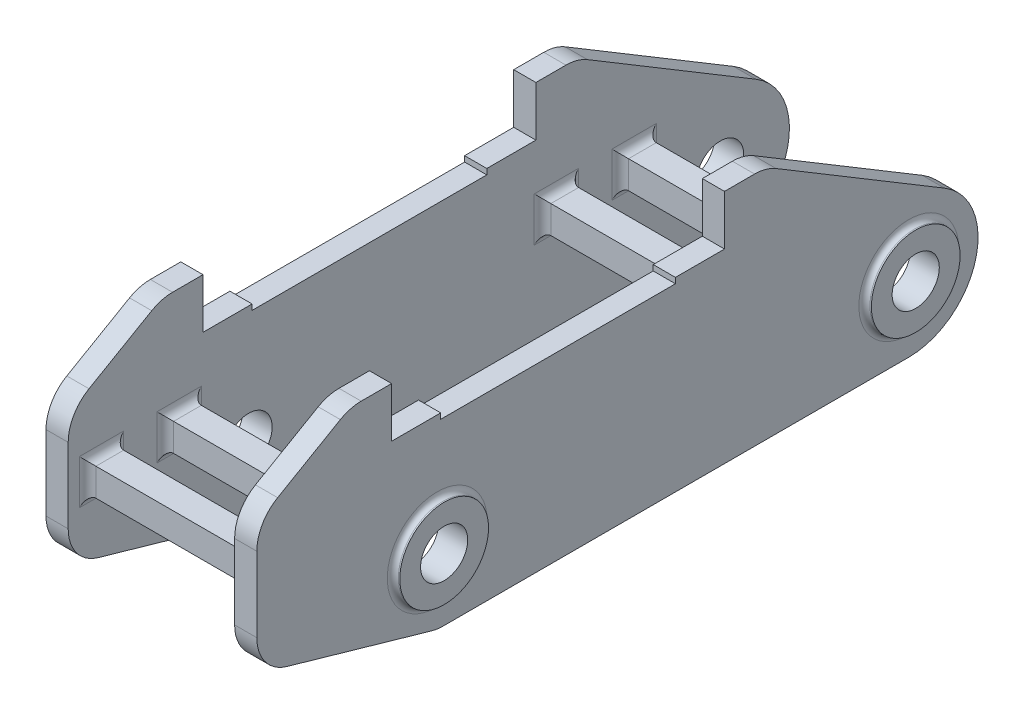
SolidWorks part; units mm, degrees
material "1.0060 (E335)"
ref_plane "Płaszczyzna przednia" through (0, 0, 0) normal (0, 0, 1) x (1, 0, 0)
ref_plane "Płaszczyzna górna" through (0, 0, 0) normal (0, 1, 0) x (1, 0, 0)
ref_plane "Płaszczyzna prawa" through (0, 0, 0) normal (1, 0, 0) x (0, 0, -1)
sketch "Szkic1" plane through (0, 0, 0) normal (1, 0, 0) x (0, 0, -1)
  line L0 (0, 0) -> (-10.9808, 0)
  line L1 (-18.4808, -2.0096) -> (-41.1, -15.0688)
  line L2 (-48.6, -28.0592) -> (-48.6, -55.0494)
  line L3 (-37.7346, -69.4684) -> (14.4043, -84.4189)
  line L4 (18.5388, -85) -> (186.4307, -85)
  line L5 (199.2908, -38.6279) -> (138.569, -2.1425)
  line L6 (130.8434, 0) -> (120.0033, 0)
  line L7 (120.0033, 0) -> (120.0033, -18)
  line L8 (120.0033, -18) -> (102.3033, -18)
  line L9 (102.3033, -18) -> (102.3033, -20)
  line L10 (102.3033, -20) -> (17.7, -20)
  line L11 (17.7, -20) -> (17.7, -18)
  line L12 (17.7, -18) -> (0, -18)
  line L13 (0, -18) -> (0, 0)
  arc A0 (186.4307, -85) -> (199.2908, -38.6279) centre (186.4307, -60.0307) ccw
  circle A1 centre (16.4307, -60) radius 8.5
  circle A2 centre (186.4307, -60) radius 8.5
  arc A3 (138.569, -2.1425) -> (130.8434, 0) centre (130.8434, -15) ccw
  arc A4 (14.4043, -84.4189) -> (18.5388, -85) centre (18.5388, -70) ccw
  arc A5 (-48.6, -55.0494) -> (-37.7346, -69.4684) centre (-33.6, -55.0494) ccw
  arc A6 (-41.1, -15.0688) -> (-48.6, -28.0592) centre (-33.6, -28.0592) ccw
  arc A7 (-10.9808, 0) -> (-18.4808, -2.0096) centre (-10.9808, -15) ccw
  point P28 (135.0033, 0)
  point P31 (16.4307, -85)
  point P38 (-15, 0)
  dimension "D2" = 17
  dimension "D3" = 17
  dimension "D18" = 15
  dimension "D1" = 260
  dimension "D4" = 170
  dimension "D5" = 196
  dimension "D6" = 15
  dimension "D7" = 120
  dimension "D8" = 15
  dimension "D9" = 75
  dimension "D10" = 149
  dimension "D11" = 85
  dimension "D12" = 48.6
  dimension "D13" = 17.7
  dimension "D14" = 17.7
  dimension "D15" = 2
  dimension "D16" = 18
  dimension "D17" = 25
extrude "Dodanie-wyciągnięcie1" add sketch "Szkic1" along normal blind 8
sketch "Szkic2" plane through (8, 0, 0) normal (1, 0, 0) x (0, 0, -1)
  circle A0 centre (16.4307, -60) radius 8.5 construction
  circle A1 centre (16.4307, -60) radius 8.5
  circle A2 centre (186.4307, -60) radius 8.5 construction
  circle A3 centre (186.4307, -60) radius 8.5
  circle A4 centre (16.4307, -60) radius 16
  circle A5 centre (186.4307, -60) radius 16
  dimension "D1" = 32
  dimension "D2" = 32
extrude "Dodanie-wyciągnięcie2" add sketch "Szkic2" along normal blind 2.5
fillet "Zaokrąglenie1" radius 2 2 edges at (8, -60, -202.4307) (8, -60, -32.4307)
ref_plane "Płaszczyzna1" through (-30, 0, 0) normal (-1, 0, 0) x (0, 0, 1)
mirror "Lustro3" about plane through (-30, 0, 0) normal (-1, 0, 0) of bodies 102
sketch "Szkic3" plane through (0, 0, 0) normal (-1, 0, 0) x (0, 0, 1)
  line L0 (0, 0) -> (10.9808, 0) construction
  line L1 (3.6, -47.5) -> (13.6, -47.5)
  line L2 (3.6, -47.5) -> (3.6, -37.5)
  line L3 (3.6, -37.5) -> (13.6, -37.5)
  line L4 (13.6, -47.5) -> (13.6, -37.5)
  line L5 (31.6, -47.5) -> (41.6, -47.5)
  line L6 (31.6, -47.5) -> (31.6, -37.5)
  line L7 (31.6, -37.5) -> (41.6, -37.5)
  line L8 (41.6, -47.5) -> (41.6, -37.5)
  line L9 (-160.4, -47.5) -> (-150.4, -47.5)
  line L10 (-160.4, -47.5) -> (-160.4, -37.5)
  line L11 (-160.4, -37.5) -> (-150.4, -37.5)
  line L12 (-150.4, -47.5) -> (-150.4, -37.5)
  line L13 (-132.4, -47.5) -> (-122.4, -47.5)
  line L14 (-132.4, -47.5) -> (-132.4, -37.5)
  line L15 (-132.4, -37.5) -> (-122.4, -37.5)
  line L16 (-122.4, -47.5) -> (-122.4, -37.5)
  line L17 (48.6, -28.0592) -> (48.6, -55.0494) construction
  point P16 (13.6, -42.5)
  dimension "D1" = 42.5
  dimension "D2" = 10
  dimension "D3" = 10
  dimension "D4" = 10
  dimension "D5" = 10
  dimension "D6" = 10
  dimension "D7" = 18
  dimension "D8" = 7
  dimension "D9" = 126
  dimension "D10" = 18
extrude "Dodanie-wyciągnięcie3" add sketch "Szkic3" along normal up to next
fillet "Zaokrąglenie2" radius 3 32 edges at (0, -42.5, -122.4) (0, -42.5, -132.4) (0, -47.5, -127.4) (0, -37.5, -127.4) (0, -47.5, -155.4) (0, -42.5, -150.4) (0, -42.5, -160.4) (0, -37.5, -155.4) (0, -42.5, 41.6) (0, -42.5, 31.6) (0, -47.5, 36.6) (0, -37.5, 36.6) (0, -42.5, 13.6) (0, -42.5, 3.6) (0, -47.5, 8.6) (0, -37.5, 8.6) (-60, -42.5, 31.6) (-60, -42.5, 41.6) (-60, -47.5, 36.6) (-60, -37.5, 36.6) (-60, -42.5, 13.6) (-60, -47.5, 8.6) (-60, -42.5, 3.6) (-60, -37.5, 8.6) (-60, -42.5, -132.4) (-60, -42.5, -122.4) (-60, -47.5, -127.4) (-60, -37.5, -127.4) (-60, -42.5, -150.4) (-60, -47.5, -155.4) (-60, -42.5, -160.4) (-60, -37.5, -155.4)
